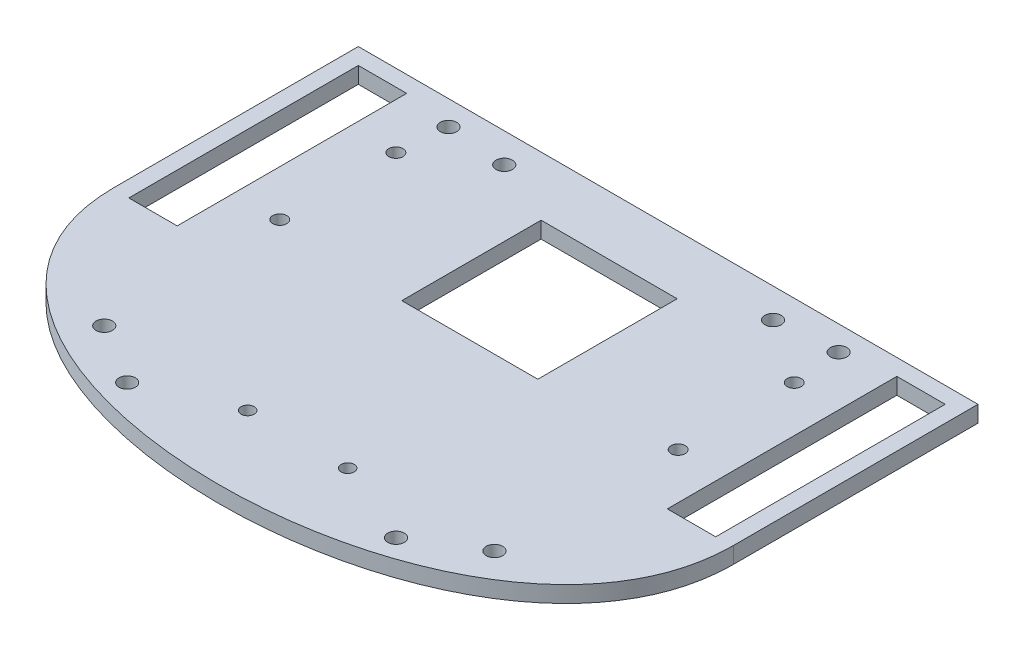
SolidWorks part; units mm, degrees
ref_plane "Front Plane" through (0, 0, 0) normal (0, 0, 1) x (1, 0, 0)
ref_plane "Top Plane" through (0, 0, 0) normal (0, 1, 0) x (1, 0, 0)
ref_plane "Right Plane" through (0, 0, 0) normal (1, 0, 0) x (0, 0, -1)
sketch "Sketch2" plane through (0, 0, 0) normal (0, 1, 0) x (1, 0, 0)
  line L4 (-48.006, -33.6908) -> (-48.006, 91.0268) construction
  line L5 (48.006, -34.798) -> (-48.006, -34.798) construction
  line L6 (48.006, -34.798) -> (48.006, 34.798) construction
  line L7 (48.006, 34.798) -> (-48.006, 34.798)
  line L8 (-48.006, -34.798) -> (-48.006, 34.798) construction
  line L9 (48.006, -34.798) -> (-48.006, 34.798) construction
  line L10 (48.006, 34.798) -> (-48.006, -34.798) construction
  line L11 (48.006, 148.5724) -> (48.006, -105.4276) construction
  line L12 (-48.006, 34.798) -> (-48.006, -3.048)
  line L13 (48.006, 34.798) -> (48.006, -3.048)
  spline S0 degree 3 poles (-48.006, -3.048) (-48.006, -45.3813) (48.006, -45.3813) (48.006, -3.048) knots 0 0 0 0 1 1 1 1
  point P0 (0, 0)
  dimension "D3" = 180
  dimension "D4" = 127
  dimension "D5" = 69.596
  dimension "D1" = 96.012
  dimension "D2" = 180
  dimension "D6" = 127
extrude "Boss-Extrude1" add sketch "Sketch2" along normal blind 2.54
sketch "Sketch3" plane through (0, 2.54, 0) normal (0, 1, 0) x (1, 0, 0)
  line L0 (0, 0) -> (0, 43.6246) construction
  line L1 (-45.466, 32.258) -> (-37.973, 32.258)
  line L2 (-45.466, 32.258) -> (-45.466, -3.302)
  line L3 (-45.466, -3.302) -> (-37.973, -3.302)
  line L4 (-37.973, 32.258) -> (-37.973, -3.302)
  line L5 (37.973, 32.258) -> (37.973, -3.302)
  line L6 (45.466, -3.302) -> (37.973, -3.302)
  line L7 (45.466, 32.258) -> (45.466, -3.302)
  line L8 (45.466, 32.258) -> (37.973, 32.258)
  line L9 (-48.006, 34.798) -> (-48.006, -3.048) construction
  line L10 (48.006, 34.798) -> (-48.006, 34.798) construction
  line L11 (-30.861, 23.4696) -> (-30.861, 5.4864) construction
  line L12 (30.861, 23.4696) -> (30.861, 5.4864) construction
  line L13 (-30.226, 30.988) -> (-30.226, -22.352) construction
  line L14 (30.226, 30.988) -> (30.226, -22.352) construction
  line L15 (0, -34.798) -> (28.6945, -34.798) construction
  line L16 (-10.541, 25.654) -> (10.541, 25.654)
  line L17 (-10.541, 25.654) -> (-10.541, 4.064)
  line L18 (-10.541, 4.064) -> (10.541, 4.064)
  line L19 (10.541, 25.654) -> (10.541, 4.064)
  line L20 (-20.828, 30.226) -> (-20.828, -28.194) construction
  circle A0 centre (-30.861, 23.4696) radius 1.0922
  circle A1 centre (-30.861, 5.4864) radius 1.0922
  circle A2 centre (-30.226, 30.988) radius 1.27
  circle A3 centre (30.861, 5.4864) radius 1.0922
  circle A4 centre (30.861, 23.4696) radius 1.0922
  circle A5 centre (-30.226, -22.352) radius 1.27
  circle A6 centre (30.226, -22.352) radius 1.27
  circle A7 centre (30.226, 30.988) radius 1.27
  circle A8 centre (-7.747, -22.606) radius 1.016
  circle A9 centre (7.747, -22.606) radius 1.016
  circle A10 centre (-20.828, 30.226) radius 1.27
  circle A11 centre (-20.828, -28.194) radius 1.27
  circle A12 centre (20.828, -28.194) radius 1.27
  circle A13 centre (20.828, 30.226) radius 1.27
  spline S1 degree 3 poles (-48.006, -3.048) (-48.006, -45.3813) (48.006, -45.3813) (48.006, -3.048) knots 0 0 0 0 1 1 1 1 construction
  point P14 (-41.7195, 32.258)
  point P20 (-30.861, 14.478)
  point P24 (-37.973, 14.478)
  point P36 (30.861, 14.478)
  point P51 (0, 0)
  point P56 (0, 0)
  dimension "D5" = 2.1844
  dimension "D6" = 2.1844
  dimension "D9" = 2.54
  dimension "D13" = 2.032
  dimension "D20" = 2.54
  dimension "D21" = 2.54
  dimension "D22" = 58.42
  dimension "D24" = 20.828
  dimension "D1" = 35.56
  dimension "D2" = 7.493
  dimension "D3" = 2.54
  dimension "D4" = 2.54
  dimension "D7" = 17.9832
  dimension "D8" = 7.112
  dimension "D10" = 3.81
  dimension "D11" = 17.78
  dimension "D12" = 53.34
  dimension "D14" = 20.32
  dimension "D15" = 21.59
  dimension "D16" = 20.32
  dimension "D17" = 15.494
  dimension "D18" = 9.144
  dimension "D19" = 12.192
  dimension "D23" = 4.572
extrude "Cut-Extrude1" cut sketch "Sketch3" against normal through all and the other way through all
